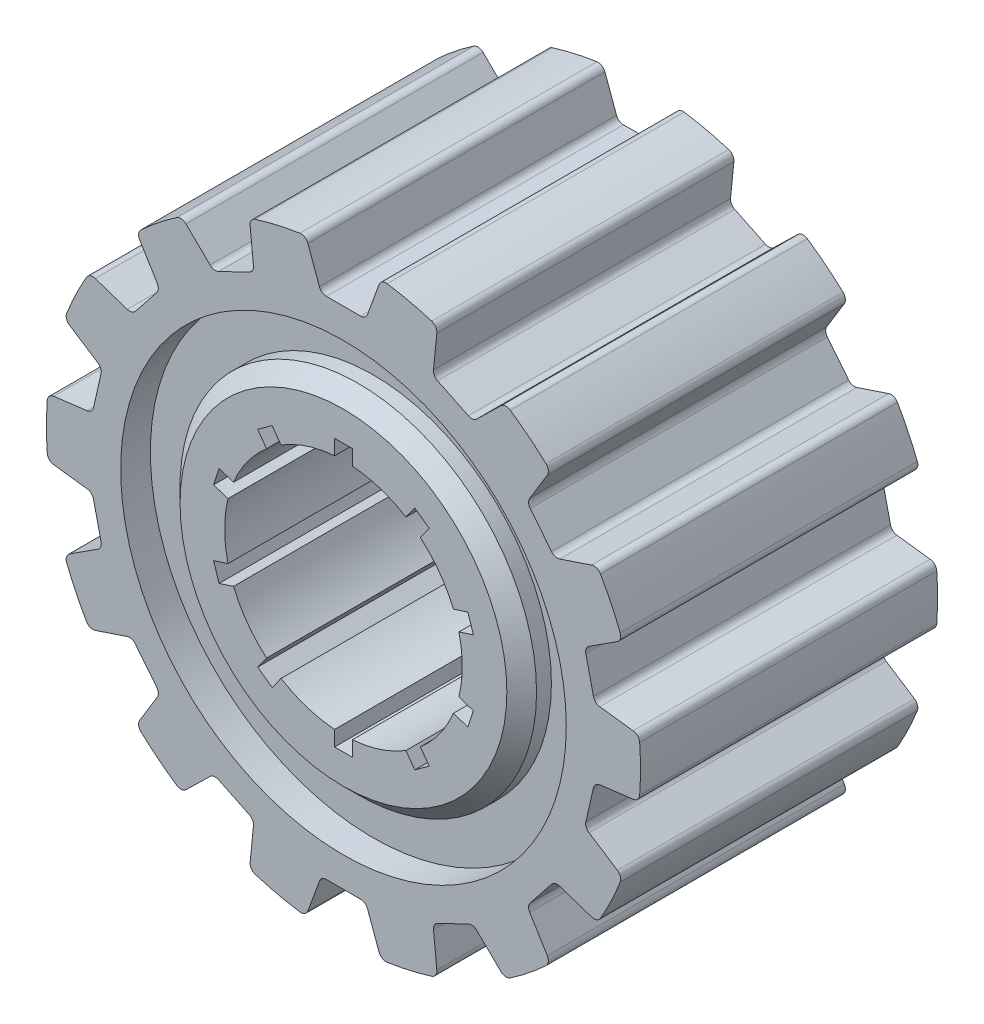
SolidWorks part; units mm, degrees
material "Alloy Steel (SS)"
ref_plane "Front " through (0, 0, 0) normal (0, 0, 1) x (1, 0, 0)
ref_plane "Top " through (0, 0, 0) normal (0, 1, 0) x (1, 0, 0)
ref_plane "Right " through (0, 0, 0) normal (1, 0, 0) x (0, 0, -1)
sketch "Sketch1" plane through (0, 0, 0) normal (0, 0, 1) x (1, 0, 0)
  line L0 (0, 0) -> (0, 8.2383) construction
  line L1 (2.8877, 3.4642) -> (2.4023, 3.8169)
  line L2 (0.3, 4.5) -> (-0.3, 4.5)
  line L3 (0.3, 4.5) -> (0.3, 3.9887)
  line L5 (-0.3, 4.5) -> (-0.3, 3.9887)
  line L6 (2.4023, 3.8169) -> (2.1018, 3.4033)
  line L7 (2.8877, 3.4642) -> (2.5872, 3.0506)
  line L8 (4.3725, 1.1053) -> (4.187, 1.6759)
  line L9 (4.187, 1.6759) -> (3.7008, 1.5179)
  line L10 (4.3725, 1.1053) -> (3.8862, 0.9473)
  line L11 (4.187, -1.6759) -> (4.3725, -1.1053)
  line L12 (4.3725, -1.1053) -> (3.8862, -0.9473)
  line L13 (4.187, -1.6759) -> (3.7008, -1.5179)
  line L14 (2.4023, -3.8169) -> (2.8877, -3.4642)
  line L15 (2.8877, -3.4642) -> (2.5872, -3.0506)
  line L16 (2.4023, -3.8169) -> (2.1018, -3.4033)
  line L17 (-0.3, -4.5) -> (0.3, -4.5)
  line L18 (0.3, -4.5) -> (0.3, -3.9887)
  line L19 (-0.3, -4.5) -> (-0.3, -3.9887)
  line L20 (-2.8877, -3.4642) -> (-2.4023, -3.8169)
  line L21 (-2.4023, -3.8169) -> (-2.1018, -3.4033)
  line L22 (-2.8877, -3.4642) -> (-2.5872, -3.0506)
  line L23 (-4.3725, -1.1053) -> (-4.187, -1.6759)
  line L24 (-4.187, -1.6759) -> (-3.7008, -1.5179)
  line L25 (-4.3725, -1.1053) -> (-3.8862, -0.9473)
  line L26 (-4.187, 1.6759) -> (-4.3725, 1.1053)
  line L27 (-4.3725, 1.1053) -> (-3.8862, 0.9473)
  line L28 (-4.187, 1.6759) -> (-3.7008, 1.5179)
  line L29 (-2.4023, 3.8169) -> (-2.8877, 3.4642)
  line L30 (-2.8877, 3.4642) -> (-2.5872, 3.0506)
  line L31 (-2.4023, 3.8169) -> (-2.1018, 3.4033)
  circle A0 centre (0, 0) radius 10
  arc A1 (-0.3, 3.9887) -> (-2.1018, 3.4033) centre (0, 0) ccw
  arc A2 (-2.5872, 3.0506) -> (-3.7008, 1.5179) centre (0, 0) ccw
  arc A3 (-3.8862, 0.9473) -> (-3.8862, -0.9473) centre (0, 0) ccw
  arc A4 (2.1018, 3.4033) -> (0.3, 3.9887) centre (0, 0) ccw
  arc A5 (3.7008, 1.5179) -> (2.5872, 3.0506) centre (0, 0) ccw
  arc A6 (3.8862, -0.9473) -> (3.8862, 0.9473) centre (0, 0) ccw
  arc A7 (2.5872, -3.0506) -> (3.7008, -1.5179) centre (0, 0) ccw
  arc A8 (0.3, -3.9887) -> (2.1018, -3.4033) centre (0, 0) ccw
  arc A9 (-2.1018, -3.4033) -> (-0.3, -3.9887) centre (0, 0) ccw
  arc A10 (-3.7008, -1.5179) -> (-2.5872, -3.0506) centre (0, 0) ccw
  dimension "D1" = 20
  dimension "D2" = 8
  dimension "D3" = 0.6
  dimension "D4" = 4.5
  dimension "D5" = 10
extrude "Boss-Extrude1" add sketch "Sketch1" along normal blind 10
sketch "Sketch2" plane through (0, 0, 10) normal (0, 0, 1) x (1, 0, 0)
  line L0 (0, 0) -> (0, 10) construction
  line L1 (-0.75, 8.5) -> (0.75, 8.5)
  line L2 (0.75, 8.5) -> (1.2666, 9.9195)
  line L3 (-0.75, 8.5) -> (-1.2666, 9.9195)
  circle A0 centre (0, 0) radius 10 construction
  circle A1 centre (0, 0) radius 10
  circle M5 centre (0, 0) radius 10
  dimension "D1" = 1.5
  dimension "D2" = 20
  dimension "D3" = 20
  dimension "D4" = 8.5
extrude "Cut-Extrude1" cut sketch "Sketch2" against normal through all contours L1 L0 A1 L3 | L0 L1 L2 M5
pattern_circular "CirPattern1" count 14 over 360 about axis through (0, 0, 0) along (0, 0, 1) of "Cut-Extrude1"
ref_plane "Plane1" through (0, 0, 5) normal (0, 0, 1) x (1, 0, 0)
sketch "Sketch3" plane through (0, 0, 5) normal (0, 0, 1) x (1, 0, 0)
  circle A0 centre (0, 0) radius 7.5
  circle A1 centre (0, 0) radius 6
  dimension "D1" = 15
  dimension "D2" = 12
extrude "Cut-Extrude2" cut sketch "Sketch3" against normal through all from offset 4 offset against normal yes
chamfer "Chamfer1" distance 0.5 angle 45 1 edges at (6, 0, 0)
mirror "Mirror1" about plane through (0, 0, 5) normal (0, 0, 1) of "Cut-Extrude2"
chamfer "Chamfer2" distance 0.5 angle 45 1 edges at (6, 0, 10)
fillet "Fillet1" radius 0.25 56 edges at (-8.5451, 5.1944, 5) (-9.3889, 3.4422, 5) (-8.12, 2.6226, 5) (-8.4538, 1.1602, 5) (-9.9526, 0.9724, 5) (-9.9526, -0.9724, 5) (-8.4538, -1.1602, 5) (-8.12, -2.6226, 5) (-9.3889, -3.4422, 5) (-8.5451, -5.1944, 5) (-7.1132, -4.7133, 5) (-6.178, -5.886, 5) (-6.9656, -7.175, 5) (-5.4451, -8.3875, 5) (-4.3637, -7.3328, 5) (-3.0123, -7.9836, 5) (-3.1627, -9.4867, 5) (-1.2666, -9.9195, 5) (-0.75, -8.5, 5) (0.75, -8.5, 5) (1.2666, -9.9195, 5) (3.1627, -9.4867, 5) (3.0123, -7.9836, 5) (4.3637, -7.3328, 5) (5.4451, -8.3875, 5) (6.9656, -7.175, 5) (6.178, -5.886, 5) (7.1132, -4.7133, 5) (8.5451, -5.1944, 5) (9.3889, -3.4422, 5) (8.12, -2.6226, 5) (8.4538, -1.1602, 5) (9.9526, -0.9724, 5) (9.9526, 0.9724, 5) (8.4538, 1.1602, 5) (8.12, 2.6226, 5) (9.3889, 3.4422, 5) (8.5451, 5.1944, 5) (7.1132, 4.7133, 5) (6.178, 5.886, 5) (6.9656, 7.175, 5) (5.4451, 8.3875, 5) (4.3637, 7.3328, 5) (3.0123, 7.9836, 5) (3.1627, 9.4867, 5) (0.75, 8.5, 5) (-0.75, 8.5, 5) (-1.2666, 9.9195, 5) (-3.1627, 9.4867, 5) (-3.0123, 7.9836, 5) (-4.3637, 7.3328, 5) (-5.4451, 8.3875, 5) (-6.9656, 7.175, 5) (-6.178, 5.886, 5) (-7.1132, 4.7133, 5) (1.2666, 9.9195, 5)
